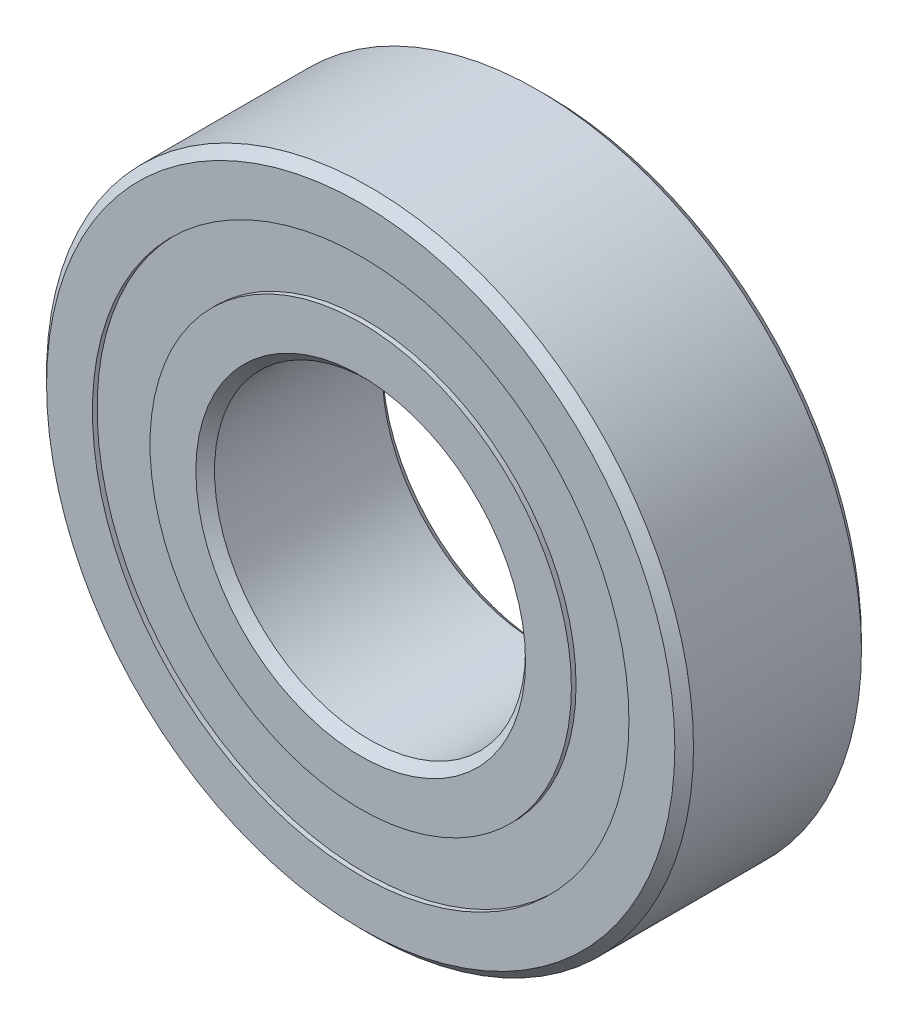
SolidWorks part; units mm, degrees
ref_plane "Front Plane" through (0, 0, 0) normal (0, 0, 1) x (1, 0, 0)
ref_plane "Top Plane" through (0, 0, 0) normal (0, 1, 0) x (1, 0, 0)
ref_plane "Right Plane" through (0, 0, 0) normal (1, 0, 0) x (0, 0, -1)
sketch "Sketch1" plane through (0, 0, 0) normal (0, 0, 1) x (1, 0, 0)
  circle A0 centre (0, 0) radius 26 construction
  circle A1 centre (0, 0) radius 12.5 construction
  dimension "OD" = 52
  dimension "ID" = 25
sketch "Sketch2" plane through (0, 0, 0) normal (1, 0, 0) x (0, 0, -1)
  line L0 (-7.5, 0) -> (7.5, 0) construction
  line L1 (0, 26) -> (0, -26) construction
  line L2 (6.75, 26) -> (-6.75, 26) construction
  line L3 (-6.75, 26) -> (-7.5, 25.25) construction
  line L4 (-7.5, 25.25) -> (-7.5, 21.5625) construction
  line L5 (-7.5, 21.5625) -> (-3.3333, 21.5625) construction
  line L6 (7.5, 21.5625) -> (3.3333, 21.5625) construction
  line L7 (7.5, 25.25) -> (7.5, 21.5625) construction
  line L8 (6.75, 26) -> (7.5, 25.25) construction
  line L9 (0, 26) -> (0, 19.25) construction
  line L10 (0, 19.25) -> (0, 12.5) construction
  line L11 (7.5, 19.25) -> (-7.5, 19.25) construction
  line L12 (-7.5, 13.25) -> (-7.5, 16.9375) construction
  line L13 (-6.75, 12.5) -> (-7.5, 13.25) construction
  line L14 (6.75, 12.5) -> (-6.75, 12.5) construction
  line L15 (6.75, 12.5) -> (7.5, 13.25) construction
  line L16 (7.5, 13.25) -> (7.5, 16.9375) construction
  line L17 (7.5, 16.9375) -> (3.3333, 16.9375) construction
  line L18 (-7.5, 16.9375) -> (-3.3333, 16.9375) construction
  line L19 (-7.5, 12.5) -> (-7.5, -12.5) construction
  line L20 (7.5, 26) -> (7.5, -26) construction
  arc A0 (-3.3333, 21.5625) -> (3.3333, 21.5625) centre (0, 19.25) cw construction
  arc A1 (-3.3333, 16.9375) -> (3.3333, 16.9375) centre (0, 19.25) ccw construction
  point P14 (0, 12.5)
  point P18 (0, 19.25)
  dimension "Approx. Ball Dia." = 8.1139
  dimension "D1" = 45
  dimension "D2" = 0.75
  dimension "D3" = 6.6667
  dimension "D4" = 2.3125
  dimension "Width" = 15
  dimension "For Shaft Diameter" = 25
  dimension "For Housing ID" = 52
sketch "Sketch3" plane through (0, 0, 0) normal (1, 0, 0) x (0, 0, -1)
  line L0 (-7.5, 25.25) -> (-7.5, 21.5625) construction
  line L1 (-6.75, 26) -> (-7.5, 25.25) construction
  line L2 (6.75, 26) -> (-6.75, 26) construction
  line L3 (6.75, 26) -> (7.5, 25.25) construction
  line L4 (7.5, 25.25) -> (7.5, 21.5625) construction
  line L5 (7.5, 21.5625) -> (3.3333, 21.5625) construction
  line L6 (-7.5, 21.5625) -> (-3.3333, 21.5625) construction
  line L7 (-7.5, 25.25) -> (-7.5, 21.5625)
  line L8 (-6.75, 26) -> (-7.5, 25.25)
  line L9 (6.75, 26) -> (-6.75, 26)
  line L10 (6.75, 26) -> (7.5, 25.25)
  line L11 (7.5, 25.25) -> (7.5, 21.5625)
  line L12 (7.5, 21.5625) -> (3.3333, 21.5625)
  line L13 (-7.5, 21.5625) -> (-3.3333, 21.5625)
  line L14 (-7.5, 13.25) -> (-7.5, 16.9375) construction
  line L15 (-6.75, 12.5) -> (-7.5, 13.25) construction
  line L16 (6.75, 12.5) -> (-6.75, 12.5) construction
  line L17 (6.75, 12.5) -> (7.5, 13.25) construction
  line L18 (7.5, 13.25) -> (7.5, 16.9375) construction
  line L19 (7.5, 16.9375) -> (3.3333, 16.9375) construction
  line L20 (-7.5, 16.9375) -> (-3.3333, 16.9375) construction
  line L21 (-7.5, 13.25) -> (-7.5, 16.9375)
  line L22 (-6.75, 12.5) -> (-7.5, 13.25)
  line L23 (6.75, 12.5) -> (-6.75, 12.5)
  line L24 (6.75, 12.5) -> (7.5, 13.25)
  line L25 (7.5, 13.25) -> (7.5, 16.9375)
  line L26 (7.5, 16.9375) -> (3.3333, 16.9375)
  line L27 (-7.5, 16.9375) -> (-3.3333, 16.9375)
  arc A0 (3.3333, 21.5625) -> (-3.3333, 21.5625) centre (0, 19.25) ccw construction
  arc A1 (3.3333, 21.5625) -> (-3.3333, 21.5625) centre (0, 19.25) ccw
  arc A2 (-3.3333, 16.9375) -> (3.3333, 16.9375) centre (0, 19.25) ccw construction
  arc A3 (-3.3333, 16.9375) -> (3.3333, 16.9375) centre (0, 19.25) ccw
revolve "Revolve1" add sketch "Sketch3" angle 360 about L0
sketch "Sketch4" plane through (0, 0, 0) normal (1, 0, 0) x (0, 0, -1)
  line L0 (-4.0569, 19.25) -> (4.0569, 19.25)
  arc A2 (-4.0569, 19.25) -> (4.0569, 19.25) centre (0, 19.25) cw
  arc A3 (3.3333, 21.5625) -> (-3.3333, 21.5625) centre (0, 19.25) ccw construction
revolve "Revolve2" add sketch "Sketch4" angle 360 about L0
pattern_circular "CirPattern1" count 10 over 360 about axis through (0, 0, 0) along (0, 0, 1) of bodies 104
sketch "Sketch5" plane through (0, 0, 0) normal (1, 0, 0) x (0, 0, -1)
  line L0 (-7.5, 21.5625) -> (-3.3333, 21.5625) construction
  line L1 (-7.125, 21.5625) -> (-4.0569, 21.5625)
  line L2 (-7.125, 21.5625) -> (-7.125, 16.9375)
  line L3 (-7.125, 16.9375) -> (-4.0569, 16.9375)
  line L4 (-4.0569, 21.5625) -> (-4.0569, 16.9375)
  line L6 (7.5, 21.5625) -> (3.3333, 21.5625) construction
  line L7 (7.125, 21.5625) -> (4.0569, 21.5625)
  line L8 (7.125, 21.5625) -> (7.125, 16.9375)
  line L9 (7.125, 16.9375) -> (4.0569, 16.9375)
  line L10 (4.0569, 21.5625) -> (4.0569, 16.9375)
  line L12 (-6.75, 26) -> (-7.5, 25.25) construction
  line L13 (-7.5, 16.9375) -> (-3.3333, 16.9375) construction
  line L14 (7.5, 16.9375) -> (3.3333, 16.9375) construction
  point P18 (-7.125, 25.625)
revolve "Revolve3" add sketch "Sketch5" angle 360 about L0
equation "\"D2@Sketch2\"= \"Width@Sketch2\" * .05"
equation "\"D3@Sketch2\"=\"Width@Sketch2\" / 2.25"
equation "\"D4@Sketch2\"=( \"OD@Sketch1\" - \"Width@Sketch2\" ) *.5 *.125"
equation "\"Approx. No. of Balls\"= ( pi * \"OD@Sketch1\" ) * .5 / \"Approx. Ball Dia.@Sketch2\""
equation "\"Balls@CirPattern1\"=\"Approx. No. of Balls\""
